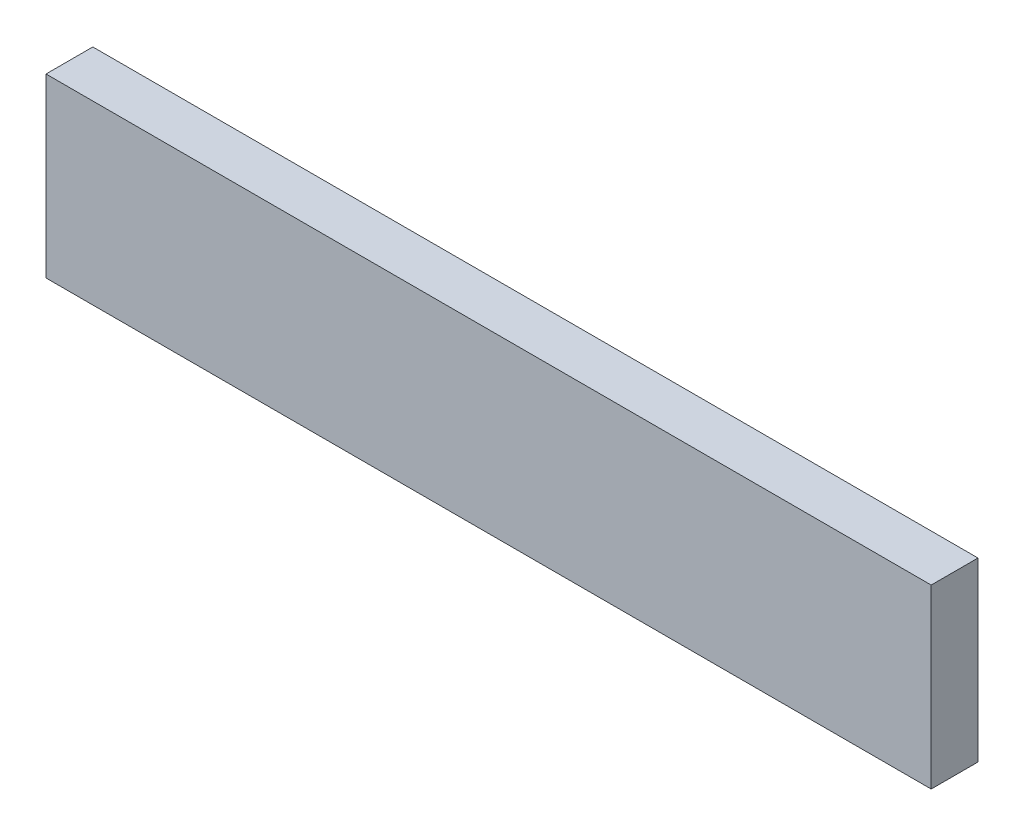
SolidWorks part; units mm, degrees
ref_plane "Front Plane" through (0, 0, 0) normal (0, 0, 1) x (1, 0, 0)
ref_plane "Top Plane" through (0, 0, 0) normal (0, 1, 0) x (1, 0, 0)
ref_plane "Right Plane" through (0, 0, 0) normal (1, 0, 0) x (0, 0, -1)
sketch "Sketch1" plane through (0, 0, 0) normal (1, 0, 0) x (0, 0, -1)
  line L0 (-0.1325, 0.5) -> (0.1325, -0.5) construction
  line L1 (0.1325, -0.5) -> (-0.1325, -0.5)
  line L2 (0.1325, -0.5) -> (0.1325, 0.5)
  line L3 (0.1325, 0.5) -> (-0.1325, 0.5)
  line L4 (-0.1325, -0.5) -> (-0.1325, 0.5)
  line L5 (0.1325, 0.5) -> (-0.1325, -0.5) construction
  point P5 (0, 0)
  dimension "DetectionLine_Y" = 1
  dimension "DetectionLine_Z" = 0.265
extrude "Boss-Extrude1" add sketch "Sketch1" along normal mid plane 5.01
